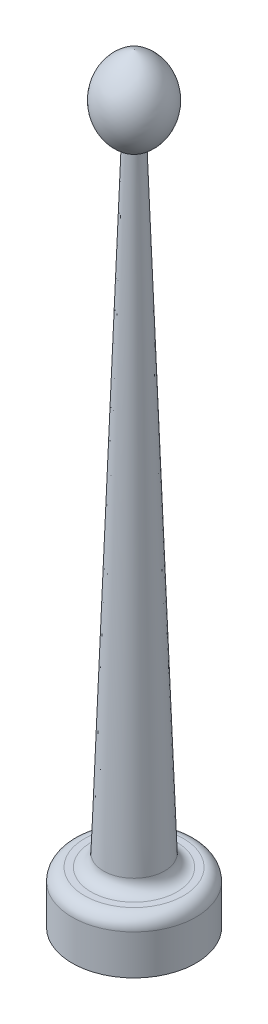
SolidWorks part; units mm, degrees
ref_plane "Alzado" through (0, 0, 0) normal (0, 0, 1) x (1, 0, 0)
ref_plane "Planta" through (0, 0, 0) normal (0, 1, 0) x (1, 0, 0)
ref_plane "Vista lateral" through (0, 0, 0) normal (1, 0, 0) x (0, 0, -1)
sketch "Croquis1" plane through (0, 0, 0) normal (0, 0, 1) x (1, 0, 0)
  line L0 (0, 0) -> (2.5, 0)
  line L1 (2.5, 0) -> (2.5, 1.608)
  line L2 (2, 2.108) -> (1.7328, 2.108)
  line L3 (1.2331, 2.5905) -> (0.3703, 27.3)
  line L4 (0, 0) -> (0, 30.6952) construction
  line L5 (0, 0) -> (0, 30.6952)
  arc A0 (0.3703, 27.3) -> (0, 30.6952) centre (-0.5141, 28.9213) ccw
  arc A1 (2.5, 1.608) -> (2, 2.108) centre (2, 1.608) ccw
  arc A2 (1.7328, 2.108) -> (1.2331, 2.5905) centre (1.7328, 2.608) cw
  point P10 (2.5, 2.108)
  point P13 (1.25, 2.108)
  point P14 (0, 0)
  point P15 (0.3658, 27.4294)
  point P16 (0, 30.6952)
  point P17 (0.3703, 27.3)
  dimension "D4" = 0.5
  dimension "D1" = 2.5
  dimension "D2" = 1.25
  dimension "D3" = 92
  dimension "D5" = 2.108
revolve "Revolución1" add sketch "Croquis1" angle 360 about L4
